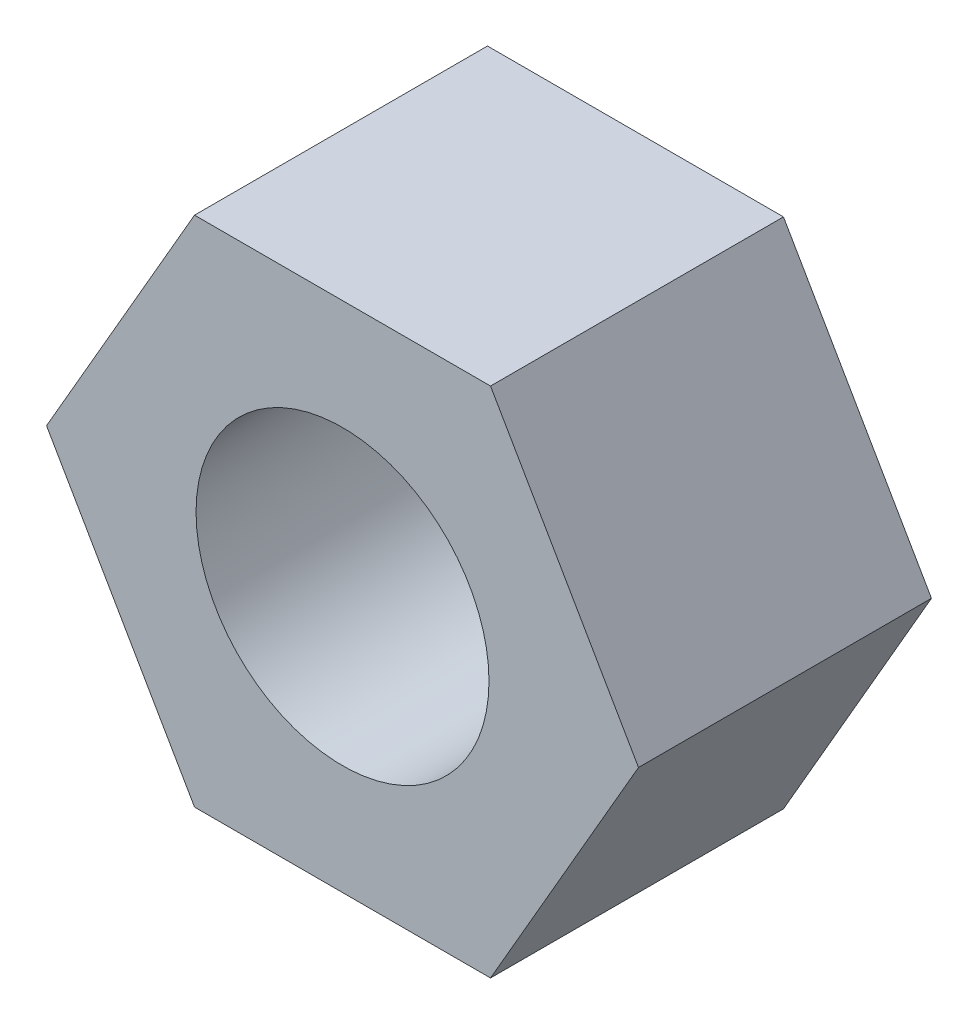
SolidWorks part; units mm, degrees
ref_plane "Front Plane" through (0, 0, 0) normal (0, 0, 1) x (1, 0, 0)
ref_plane "Top Plane" through (0, 0, 0) normal (0, 1, 0) x (1, 0, 0)
ref_plane "Right Plane" through (0, 0, 0) normal (1, 0, 0) x (0, 0, -1)
sketch "Sketch1" plane through (0, 0, 0) normal (0, 0, 1) x (1, 0, 0)
  line L1 (6.4158, -11.1125) -> (12.8316, 0)
  line L2 (12.8316, 0) -> (6.4158, 11.1125)
  line L3 (6.4158, 11.1125) -> (-6.4158, 11.1125)
  line L4 (-6.4158, 11.1125) -> (-12.8316, 0)
  line L5 (-12.8316, 0) -> (-6.4158, -11.1125)
  line L6 (-6.4158, -11.1125) -> (6.4158, -11.1125)
  circle A0 centre (0, 0) radius 11.1125 construction
  circle A1 centre (0, 0) radius 6.35
  dimension "D2" = 12.7
  dimension "D1" = 22.225
extrude "Boss-Extrude1" add sketch "Sketch1" along normal blind 12.7
